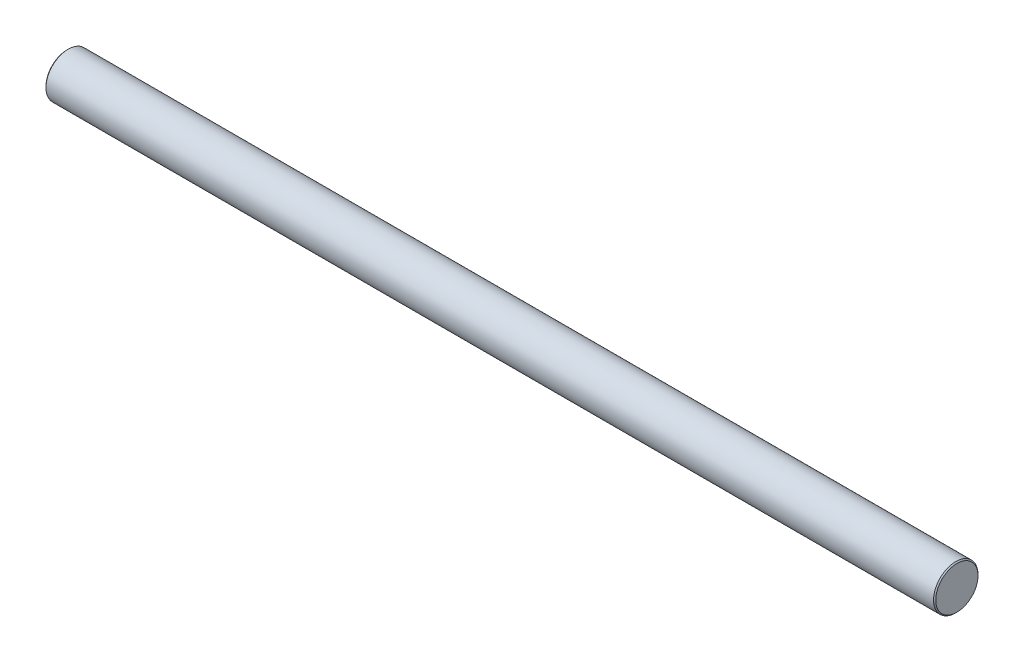
SolidWorks part; units mm, degrees
ref_plane "Alzado" through (0, 0, 0) normal (0, 0, 1) x (1, 0, 0)
ref_plane "Planta" through (0, 0, 0) normal (0, 1, 0) x (1, 0, 0)
ref_plane "Vista lateral" through (0, 0, 0) normal (1, 0, 0) x (0, 0, -1)
sketch "Croquis1" plane through (0, 0, 0) normal (1, 0, 0) x (0, 0, -1)
  circle A0 centre (0, 0) radius 1
extrude "Saliente-Extruir1" add sketch "Croquis1" along normal blind 40
chamfer "Chaflán1" distance 0.05 angle 45 2 edges at (0, 0, -1) (40, 0, -1)
